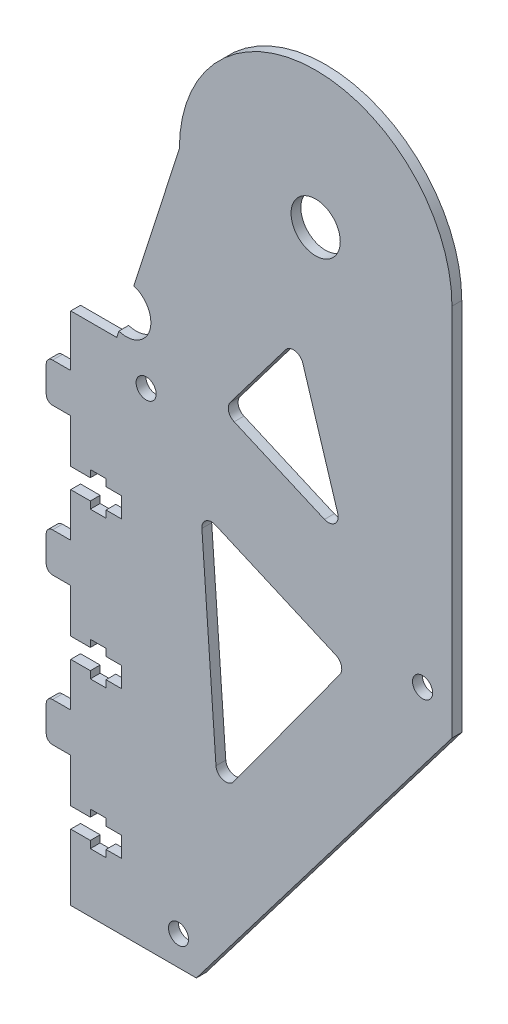
SolidWorks part; units mm, degrees
ref_plane "前视基准面" through (0, 0, 0) normal (0, 0, 1) x (1, 0, 0)
ref_plane "上视基准面" through (0, 0, 0) normal (0, 1, 0) x (1, 0, 0)
ref_plane "右视基准面" through (0, 0, 0) normal (1, 0, 0) x (0, 0, -1)
sketch "草图1" plane through (0, 0, 0) normal (0, 0, 1) x (1, 0, 0)
  line L4 (298.5456, -83.8944) -> (298.5456, -92.8418)
  line L11 (348.537, 4.3962) -> (298.542, 5.1056) construction
  line L15 (298.5456, -96.9418) -> (302.5456, -96.9418)
  line L16 (302.5456, -96.9418) -> (302.5456, -98.3918)
  line L17 (302.5456, -98.3918) -> (305.7456, -98.3918)
  line L18 (305.7456, -98.3918) -> (305.7456, -96.9418)
  line L19 (305.7456, -96.9418) -> (308.9456, -96.9418)
  line L20 (308.9456, -96.9418) -> (308.9456, -92.8418)
  line L21 (308.9456, -92.8418) -> (305.7456, -92.8418)
  line L22 (305.7456, -92.8418) -> (305.7456, -91.3918)
  line L23 (305.7456, -91.3918) -> (302.5456, -91.3918)
  line L24 (302.5456, -91.3918) -> (302.5456, -92.8418)
  line L25 (302.5456, -92.8418) -> (298.5456, -92.8418)
  line L27 (298.5456, -94.8944) -> (302.5431, -94.8944) construction
  line L28 (298.5456, -109.8944) -> (303.5456, -109.8944) construction
  line L29 (303.5456, -113.8944) -> (293.5456, -113.8944) construction
  line L30 (303.5456, -113.8944) -> (303.5456, -105.8944) construction
  line L31 (303.5456, -105.8944) -> (293.5456, -105.8944) construction
  line L32 (293.5456, -113.8944) -> (293.5456, -105.8944)
  line L33 (303.5456, -113.8944) -> (293.5456, -105.8944) construction
  line L34 (303.5456, -105.8944) -> (293.5456, -113.8944) construction
  line L35 (302.5456, -126.947) -> (298.5456, -126.947)
  line L36 (298.5456, -122.847) -> (302.5456, -122.847)
  line L37 (302.5456, -128.397) -> (302.5456, -126.947)
  line L38 (305.7456, -128.397) -> (302.5456, -128.397)
  line L39 (305.7456, -126.947) -> (305.7456, -128.397)
  line L40 (308.9456, -126.947) -> (305.7456, -126.947)
  line L41 (308.9456, -122.847) -> (308.9456, -126.947)
  line L42 (305.7456, -122.847) -> (308.9456, -122.847)
  line L43 (305.7456, -121.397) -> (305.7456, -122.847)
  line L44 (302.5456, -121.397) -> (305.7456, -121.397)
  line L45 (302.5456, -122.847) -> (302.5456, -121.397)
  line L46 (293.5456, -75.8944) -> (293.5456, -83.8944)
  line L47 (302.5456, -62.8418) -> (298.5456, -62.8418)
  line L48 (298.5456, -66.9418) -> (302.5456, -66.9418)
  line L49 (302.5456, -66.9418) -> (302.5456, -68.3918)
  line L50 (302.5456, -68.3918) -> (305.7456, -68.3918)
  line L51 (305.7456, -68.3918) -> (305.7456, -66.9418)
  line L52 (305.7456, -66.9418) -> (308.9456, -66.9418)
  line L53 (308.9456, -66.9418) -> (308.9456, -62.8418)
  line L54 (308.9456, -62.8418) -> (305.7456, -62.8418)
  line L55 (305.7456, -62.8418) -> (305.7456, -61.3918)
  line L56 (305.7456, -61.3918) -> (302.5456, -61.3918)
  line L57 (302.5456, -61.3918) -> (302.5456, -62.8418)
  line L58 (293.5456, -83.8944) -> (298.5456, -83.8944)
  line L59 (293.5456, -75.8944) -> (298.5456, -75.8944)
  line L60 (298.5456, -75.8944) -> (298.5456, -66.9418)
  line L63 (298.5456, -105.8944) -> (293.5456, -105.8944)
  line L64 (293.5456, -113.8944) -> (298.5456, -113.8944)
  line L65 (298.5456, -113.8944) -> (298.5456, -122.847)
  line L66 (308.9456, -64.8918) -> (305.2429, -64.8918) construction
  line L67 (293.5456, -45.8892) -> (298.5456, -45.8892)
  line L68 (293.5456, -53.8892) -> (293.5456, -45.8892)
  line L69 (293.5456, -53.8892) -> (298.5456, -53.8892)
  line L70 (298.5456, -53.8892) -> (298.5456, -62.8418)
  line L78 (298.5456, -126.947) -> (298.5456, -140.447)
  line L79 (298.5456, -140.447) -> (324.1889, -140.447)
  line L81 (376.3586, 4.3962) -> (376.3586, -71.947)
  line L84 (376.3586, -71.947) -> (324.1889, -140.447)
  line L85 (298.5456, -45.8892) -> (298.5456, -35.347)
  line L87 (298.5456, -35.347) -> (307.937, -35.347)
  line L88 (307.937, -35.347) -> (320.7154, 4.3962)
  line L89 (320.5456, -134.447) -> (313.937, -41.347) construction
  line L90 (313.937, -41.347) -> (370.3586, -65.947) construction
  line L91 (370.3586, -65.947) -> (320.5456, -134.447) construction
  line L92 (354.9473, -70.1368) -> (328.5796, -106.3961)
  line L93 (328.5796, -106.3961) -> (325.0814, -57.1152)
  line L94 (325.0814, -57.1152) -> (354.9473, -70.1368)
  line L95 (370.3586, -65.947) -> (348.537, 4.3962) construction
  line L96 (348.537, 4.3962) -> (313.937, -41.347) construction
  line L97 (329.5711, -37.2544) -> (354.3373, -48.0525)
  line L98 (354.3373, -48.0525) -> (344.7587, -17.1754)
  line L99 (344.7587, -17.1754) -> (329.5711, -37.2544)
  line L100 (348.537, 4.3962) -> (337.1349, 16.1265) construction
  line L101 (298.5456, -96.9418) -> (298.5456, -105.8944)
  line L104 (376.3586, -71.947) -> (376.3586, -11.3546) construction
  circle A11 centre (348.537, 4.3962) radius 5.0225
  circle A14 centre (348.537, 4.3962) radius 27.8216 construction
  circle A23 centre (348.5373, 24.4573) radius 2.05 construction
  circle A24 centre (320.5456, -134.447) radius 2.05
  circle A25 centre (370.3586, -65.947) radius 2.05
  circle A26 centre (313.937, -41.347) radius 2.05
  circle A27 centre (348.537, 4.3962) radius 12 construction
  circle A28 centre (340.173, 13.001) radius 1.65 construction
  arc A39 (320.7154, 4.3962) -> (376.3586, 4.3962) centre (348.537, 4.3962) cw
  circle A43 centre (357.1418, 12.7602) radius 1.65 construction
  circle A44 centre (356.901, -4.2086) radius 1.65 construction
  circle A45 centre (339.9322, -3.9678) radius 1.65 construction
  point P20 (300.5444, -94.8944)
  point P30 (298.5456, -109.8944)
  dimension "D3" = 4.1
  dimension "D4" = 10.045
  dimension "D5" = 3.2
  dimension "D6" = 50
  dimension "D15" = 22
  dimension "D17" = 6
  dimension "D19" = 6
  dimension "D23" = 24
  dimension "D25" = 3.3
  dimension "D7" = 4
  dimension "D8" = 4
  dimension "D9" = 2.0526
  dimension "D10" = 15
  dimension "D11" = 8
  dimension "D12" = 10
  dimension "D13" = 100
  dimension "D14" = 13.5
  dimension "D16" = 6
  dimension "D18" = 6
  dimension "D20" = 6
  dimension "D24" = 45
  dimension "D30" = 7
  dimension "D21" = 10
  dimension "D22" = 10
extrude "凸台-拉伸1" add sketch "草图1" along normal blind 2
sketch "草图2" plane through (298.5456, 0, 0) normal (-1, 0, 0) x (0, 0, 1)
  line L0 (1, -66.9418) -> (1, -62.8418)
  line L1 (2, -66.9418) -> (0, -66.9418) construction
  line L2 (2, -62.8418) -> (0, -62.8418) construction
  circle A0 centre (1, -64.8918) radius 2.05
fillet "圆角1" radius 2 6 edges at (344.7587, -17.1754, 1) (329.5711, -37.2544, 1) (354.3373, -48.0525, 1) (325.0814, -57.1152, 1) (328.5796, -106.3961, 1) (354.9473, -70.1368, 1)
fillet "圆角2" radius 1.3 6 edges at (293.5456, -45.8892, 1) (293.5456, -53.8892, 1) (293.5456, -83.8944, 1) (293.5456, -75.8944, 1) (293.5456, -113.8944, 1) (293.5456, -105.8944, 1)
sketch "草图3" plane through (0, 0, 0) normal (0, 0, -1) x (-1, 0, 0)
  line L2 (-320.7154, 4.3962) -> (-307.937, -35.347) construction
  circle A1 centre (-309.8999, -29.242) radius 5
extrude "切除-拉伸1" cut sketch "草图3" against normal blind 2
